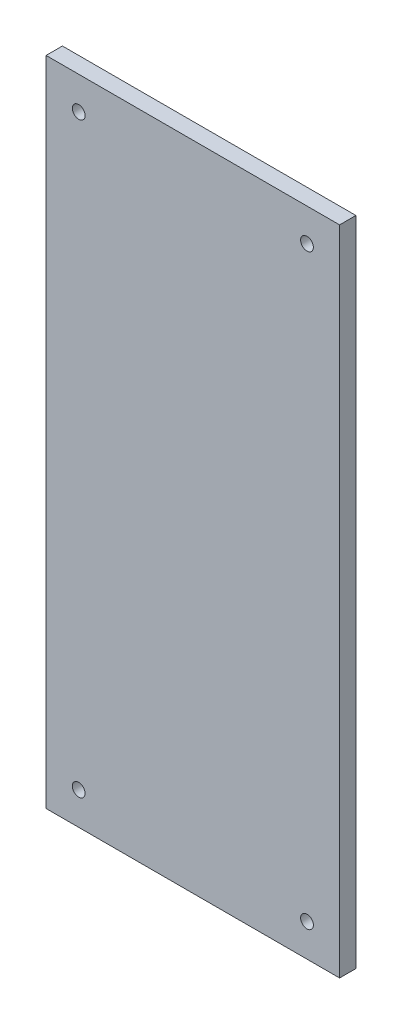
SolidWorks part; units mm, degrees
material "6061-T6 (SS)"
ref_plane "Front Plane" through (0, 0, 0) normal (0, 0, 1) x (1, 0, 0)
ref_plane "Top Plane" through (0, 0, 0) normal (0, 1, 0) x (1, 0, 0)
ref_plane "Right Plane" through (0, 0, 0) normal (1, 0, 0) x (0, 0, -1)
sketch "Sketch1" plane through (0, 0, 0) normal (0, 0, 1) x (1, 0, 0)
  line L1 (0, 0) -> (114.3, 0)
  line L2 (0, 0) -> (0, 254)
  line L3 (0, 254) -> (114.3, 254)
  line L4 (114.3, 0) -> (114.3, 254)
  dimension "D1" = 114.3
  dimension "D2" = 254
extrude "Boss-Extrude1" add sketch "Sketch1" along normal mid plane 6.35
sketch "Sketch2" plane through (0, 0, 3.175) normal (0, 0, 1) x (1, 0, 0)
  line L0 (0, 254) -> (0, 0) construction
  line L1 (114.3, 254) -> (0, 254) construction
  line L2 (114.3, 0) -> (114.3, 254) construction
  line L3 (0, 0) -> (114.3, 0) construction
  circle A0 centre (12.7, 241.3) radius 2.4892
  circle A1 centre (12.7, 12.7) radius 2.4892
  circle A2 centre (101.6, 241.3) radius 2.4892
  circle A3 centre (101.6, 12.7) radius 2.4892
  point P8 (0, 0)
  point P9 (0, 0)
  point P10 (0, 0)
  point P11 (0, 0)
  dimension "D1" = 4.9784
  dimension "D2" = 12.7
  dimension "D3" = 12.7
  dimension "D4" = 12.7
  dimension "D5" = 12.7
extrude "Cut-Extrude1" cut sketch "Sketch2" against normal through all
